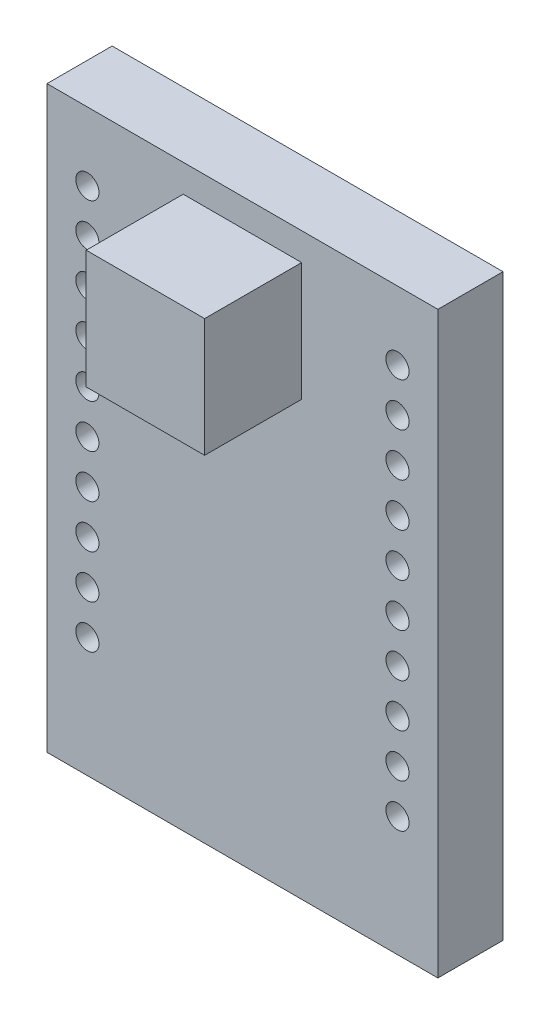
SolidWorks part; units mm, degrees
ref_plane "Front Plane" through (0, 0, 0) normal (0, 0, 1) x (1, 0, 0)
ref_plane "Top Plane" through (0, 0, 0) normal (0, 1, 0) x (1, 0, 0)
ref_plane "Right Plane" through (0, 0, 0) normal (1, 0, 0) x (0, 0, -1)
sketch "Sketch1" plane through (0, 0, 0) normal (0, 0, 1) x (1, 0, 0)
  line L1 (-13.5, 20) -> (13.5, 20)
  line L2 (-13.5, 20) -> (-13.5, -20)
  line L3 (-13.5, -20) -> (13.5, -20)
  line L4 (13.5, 20) -> (13.5, -20)
  line L5 (-13.5, 20) -> (13.5, -20) construction
  line L6 (-13.5, -20) -> (13.5, 20) construction
  point P0 (0, 0)
  dimension "D1" = 27
  dimension "D2" = 40
extrude "Boss-Extrude1" add sketch "Sketch1" along normal blind 4.5
sketch "Sketch2" plane through (0, 0, 4.5) normal (0, 0, 1) x (1, 0, 0)
  line L1 (-4.09, 18.09) -> (4.09, 18.09)
  line L2 (-4.09, 18.09) -> (-4.09, 9.91)
  line L3 (-4.09, 9.91) -> (4.09, 9.91)
  line L4 (4.09, 18.09) -> (4.09, 9.91)
  line L5 (-4.09, 18.09) -> (4.09, 9.91) construction
  line L6 (-4.09, 9.91) -> (4.09, 18.09) construction
  point P0 (0, 14)
  dimension "D1" = 8.18
  dimension "D2" = 8.18
  dimension "D3" = 14
extrude "Boss-Extrude2" add sketch "Sketch2" along normal blind 6.7
sketch "Sketch3" plane through (0, 0, 4.5) normal (0, 0, 1) x (1, 0, 0)
  circle A0 centre (10.7093, 15.2711) radius 0.8
  circle A1 centre (10.7093, 12.2711) radius 0.8
  circle A2 centre (10.7093, 9.2711) radius 0.8
  circle A3 centre (10.7093, 6.2711) radius 0.8
  circle A4 centre (10.7093, 3.2711) radius 0.8
  circle A5 centre (10.7093, 0.2711) radius 0.8
  circle A6 centre (10.7093, -2.7289) radius 0.8
  circle A7 centre (10.7093, -5.7289) radius 0.8
  circle A8 centre (10.7093, -8.7289) radius 0.8
  circle A9 centre (10.7093, -11.7289) radius 0.8
  point P5 (10.7093, -16.2289)
  point P13 (10.7093, -22.2289)
  point P18 (10.7093, -28.2289)
  point P23 (10.7093, -34.2289)
  point P28 (10.7093, -40.2289)
  dimension "D1" = 1.6
  dimension "D2" = 1.6
  dimension "D3" = 3
  dimension "D4" = 5
extrude "Cut-Extrude1" cut sketch "Sketch3" against normal blind 6.7
mirror "Mirror1" about plane through (0, 0, 0) normal (1, 0, 0) of "Cut-Extrude1"
